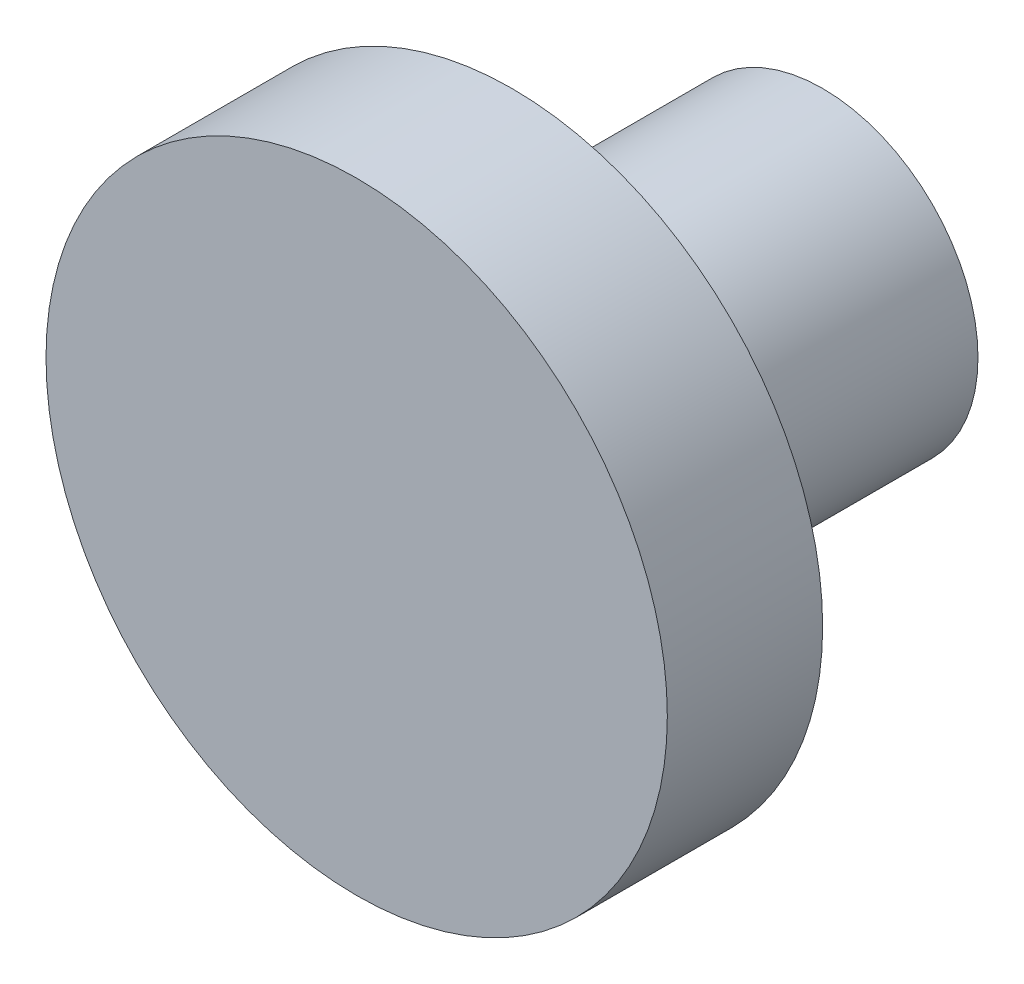
SolidWorks part; units mm, degrees
ref_plane "Plan de face" through (0, 0, 0) normal (0, 0, 1) x (1, 0, 0)
ref_plane "Plan de dessus" through (0, 0, 0) normal (0, 1, 0) x (1, 0, 0)
ref_plane "Plan de droite" through (0, 0, 0) normal (1, 0, 0) x (0, 0, -1)
sketch "Sketch1" plane through (0, 0, 0) normal (0, 0, 1) x (1, 0, 0)
  circle A0 centre (0, 0) radius 20
  dimension "D1" = 40
extrude "Boss-Extrude2" add sketch "Sketch1" along normal blind 10
sketch "Sketch3" plane through (0, 0, 0) normal (0, 0, -1) x (-1, 0, 0)
  circle A0 centre (0, 0) radius 10
  dimension "D1" = 20
extrude "Boss-Extrude3" add sketch "Sketch3" along normal blind 20
